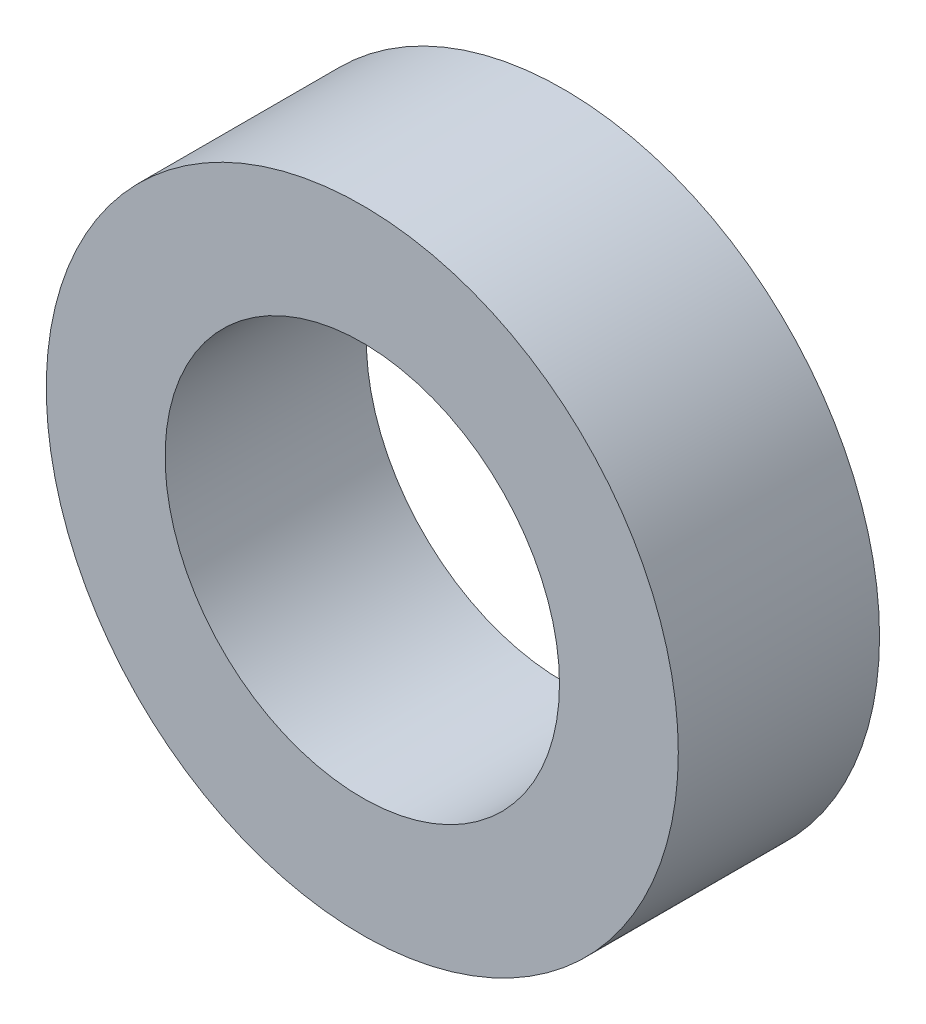
SolidWorks part; units mm, degrees
ref_plane "Front Plane" through (0, 0, 0) normal (0, 0, 1) x (1, 0, 0)
ref_plane "Top Plane" through (0, 0, 0) normal (0, 1, 0) x (1, 0, 0)
ref_plane "Right Plane" through (0, 0, 0) normal (1, 0, 0) x (0, 0, -1)
sketch "Sketch1" plane through (0, 0, 0) normal (0, 0, 1) x (1, 0, 0)
  circle A0 centre (0, 0) radius 15.875
  circle A1 centre (0, 0) radius 9.906
  dimension "D1" = 31.75
  dimension "D2" = 19.812
extrude "Boss-Extrude1" add sketch "Sketch1" along normal blind 10.1092
